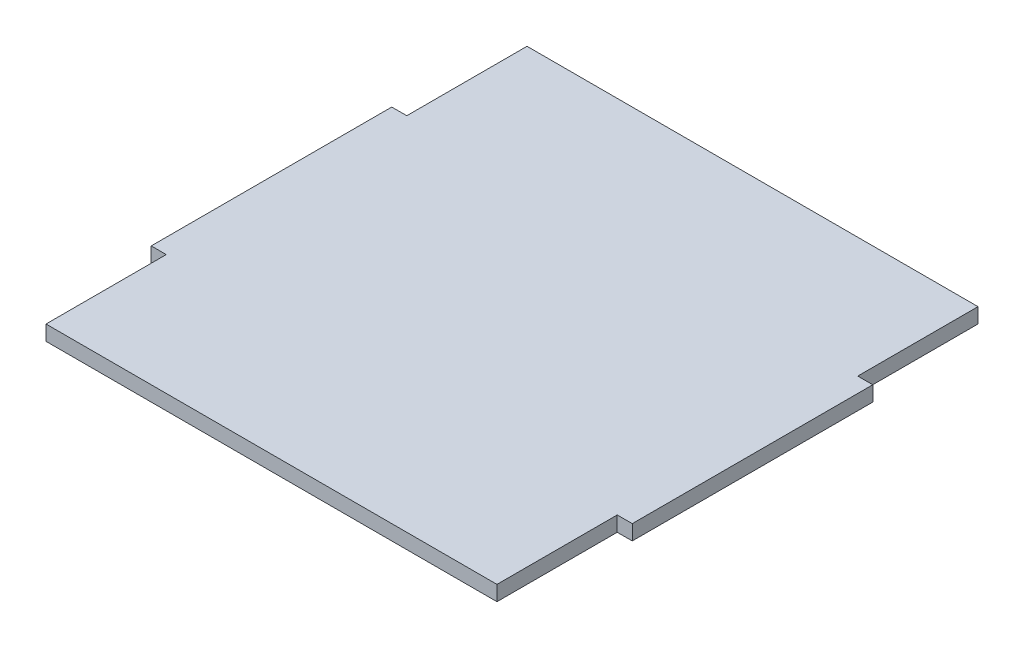
SolidWorks part; units mm, degrees
ref_plane "Front Plane" through (0, 0, 0) normal (0, 0, 1) x (1, 0, 0)
ref_plane "Top Plane" through (0, 0, 0) normal (0, 1, 0) x (1, 0, 0)
ref_plane "Right Plane" through (0, 0, 0) normal (1, 0, 0) x (0, 0, -1)
sketch "Sketch1" plane through (0, 0, 0) normal (0, 1, 0) x (1, 0, 0)
  line L0 (3.175, 76.2) -> (3.175, 101.6)
  line L1 (0, 0) -> (101.6, 0)
  line L2 (0, 0) -> (0, 101.6)
  line L3 (0, 101.6) -> (101.6, 101.6)
  line L4 (101.6, 0) -> (101.6, 101.6)
  line L5 (0, 25.4) -> (3.175, 25.4)
  line L6 (0, 25.4) -> (0, 76.2)
  line L7 (0, 76.2) -> (3.175, 76.2)
  line L9 (3.175, 25.4) -> (3.175, 0)
  line L11 (101.6, 0) -> (98.425, 0)
  line L12 (101.6, 0) -> (101.6, 25.4)
  line L13 (101.6, 25.4) -> (98.425, 25.4)
  line L14 (98.425, 0) -> (98.425, 25.4)
  line L15 (101.6, 101.6) -> (98.425, 101.6)
  line L16 (101.6, 101.6) -> (101.6, 76.2)
  line L17 (101.6, 76.2) -> (98.425, 76.2)
  line L18 (98.425, 101.6) -> (98.425, 76.2)
  point P14 (0, 0)
extrude "Boss-Extrude1" add sketch "Sketch1" along normal blind 3.175 contours L18 L3 L0 L7 L2 L5 L9 L1 L14 L13 L4 L17
